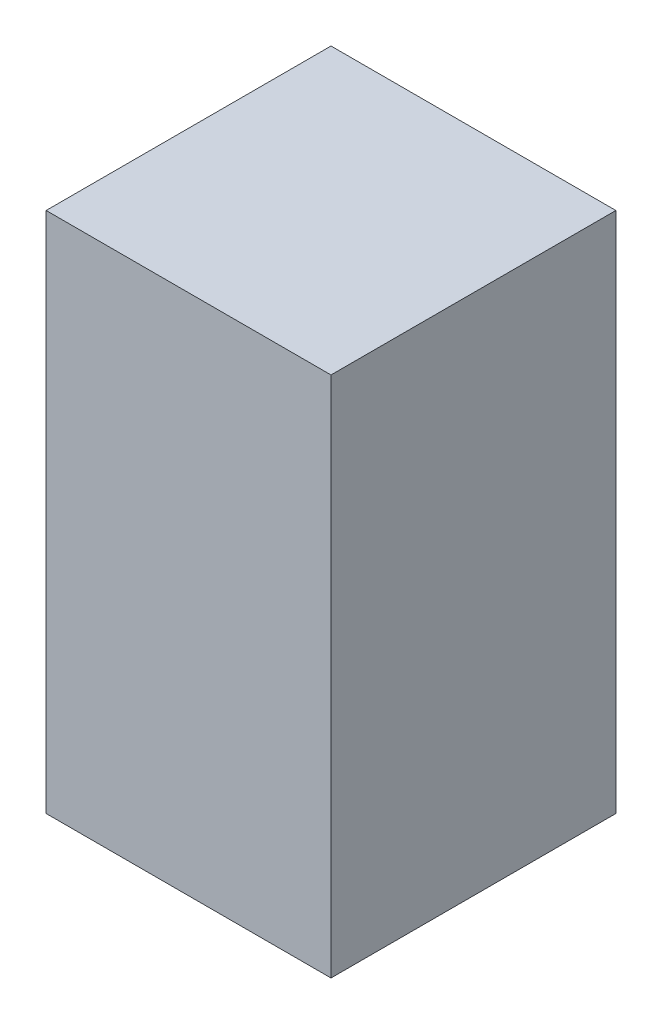
SolidWorks part; units mm, degrees
ref_plane "Front Plane" through (0, 0, 0) normal (0, 0, 1) x (1, 0, 0)
ref_plane "Top Plane" through (0, 0, 0) normal (0, 1, 0) x (1, 0, 0)
ref_plane "Right Plane" through (0, 0, 0) normal (1, 0, 0) x (0, 0, -1)
sketch "Sketch1" plane through (0, 0, 0) normal (0, 1, 0) x (1, 0, 0)
  line L1 (-30, -30) -> (30, -30)
  line L2 (-30, -30) -> (-30, 30)
  line L3 (-30, 30) -> (30, 30)
  line L4 (30, -30) -> (30, 30)
  line L5 (-30, -30) -> (30, 30) construction
  line L6 (-30, 30) -> (30, -30) construction
  point P0 (0, 0)
  dimension "D1" = 60
  dimension "D2" = 60
extrude "Boss-Extrude1" add sketch "Sketch1" along normal blind 110
